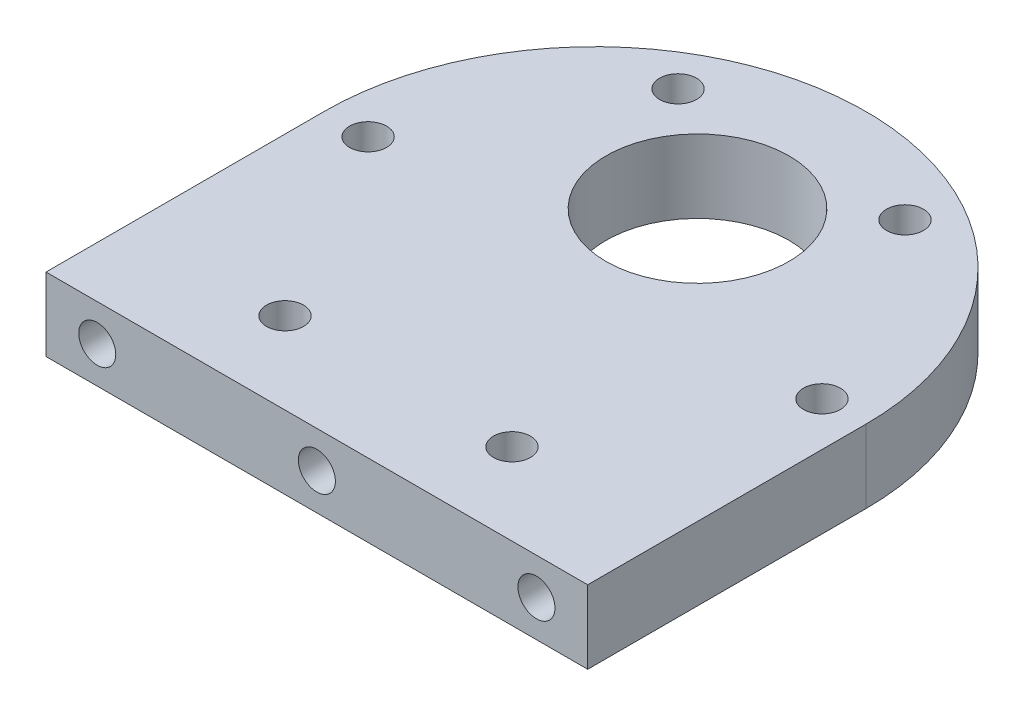
SolidWorks part; units mm, degrees
ref_plane "Plano frontal" through (0, 0, 0) normal (0, 0, 1) x (1, 0, 0)
ref_plane "Plano superior" through (0, 0, 0) normal (0, 1, 0) x (1, 0, 0)
ref_plane "Plano direito" through (0, 0, 0) normal (1, 0, 0) x (0, 0, -1)
sketch "Esboço2" plane through (0, 0, 0) normal (0, 1, 0) x (1, 0, 0)
  line L0 (10.75, 32.4234) -> (18.5, 19) construction
  line L1 (0, 0) -> (37, 0)
  line L2 (0, 0) -> (0, 19)
  line L4 (37, 0) -> (37, 19)
  line L5 (18.5, 19) -> (4.0206, 19) construction
  arc A0 (37, 19) -> (0, 19) centre (18.5, 19) ccw
  circle A1 centre (10.75, 32.4234) radius 1.265
  circle A2 centre (26.25, 32.4234) radius 1.265
  circle A3 centre (34, 19) radius 1.265
  circle A4 centre (26.25, 5.5766) radius 1.265
  circle A5 centre (10.75, 5.5766) radius 1.265
  circle A6 centre (3, 19) radius 1.265
  point P22 (18.5, 19)
  dimension "D3" = 18.5
  dimension "D4" = 2.53
  dimension "D1" = 37
  dimension "D2" = 19
  dimension "D5" = 15.5
  dimension "D6" = 60
  dimension "D7" = 6
extrude "Ressalto-extrusão1" add sketch "Esboço2" along normal blind 5
sketch "Esboço3" plane through (0, 0, 0) normal (0, -1, 0) x (1, 0, 0)
  line L0 (0, -19) -> (37, -19) construction
  line L1 (18.5, -19) -> (18.5, -26) construction
  circle A0 centre (18.5, -26) radius 6.25
  dimension "D2" = 12.5
  dimension "D1" = 7
extrude "Corte-extrusão1" cut sketch "Esboço3" against normal up to surface (5 mm away) up to face at (10.75, 5, -4.3116)
sketch "Esboço4" plane through (0, 0, 0) normal (0, 0, 1) x (1, 0, 0)
  line L0 (0, 2.5) -> (37, 2.5) construction
  line L1 (0, 5) -> (0, 0) construction
  line L2 (37, 5) -> (37, 0) construction
  line L3 (0, 5) -> (37, 5) construction
  circle A0 centre (3.5, 2.5) radius 1.265
  circle A1 centre (18.5, 2.5) radius 1.265
  circle A2 centre (33.5, 2.5) radius 1.265
  dimension "D1" = 2.53
  dimension "D2" = 3.5
  dimension "D3" = 3
extrude "Corte-extrusão2" cut sketch "Esboço4" against normal blind 12
